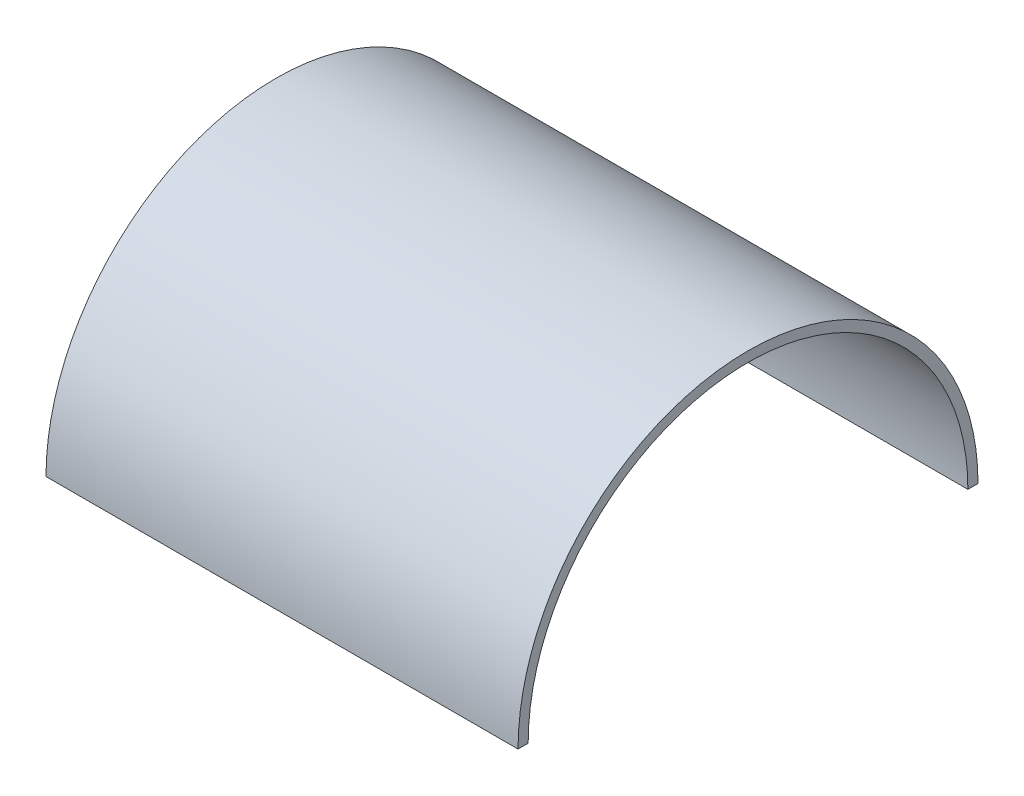
SolidWorks part; units mm, degrees
ref_plane "Front Plane" through (0, 0, 0) normal (0, 0, 1) x (1, 0, 0)
ref_plane "Top Plane" through (0, 0, 0) normal (0, 1, 0) x (1, 0, 0)
ref_plane "Right Plane" through (0, 0, 0) normal (1, 0, 0) x (0, 0, -1)
sketch "Sketch2" plane through (0, 0, 0) normal (1, 0, 0) x (0, 0, -1)
  line L0 (0, 0) -> (115.5796, 0) construction
  arc A0 (0, 0) -> (115.5796, 0) centre (57.7898, 0) cw
ref_plane "Plane1" through (0, 0, -57.7898) normal (0, 0, 1) x (1, 0, 0)
sketch "Sketch3" plane through (0, 0, -57.7898) normal (0, 0, 1) x (1, 0, 0)
  line L0 (0, 0) -> (-110.7382, 0) construction
ref_plane "Plane2" through (0, -25.0237, -43.3424) normal (0, 0.5, 0.866) x (1, 0, 0)
sketch "Sketch5" plane through (0, -25.0237, -43.3424) normal (0, 0.5, 0.866) x (1, 0, 0)
  line L0 (-61.0471, 29.1299) -> (-61.0471, 49.1687) construction
  circle A0 centre (-61.0471, 49.1687) radius 12.2637
extrude "Extrude-Thin1" add sketch "Sketch2" against normal blind 118.618 thin
